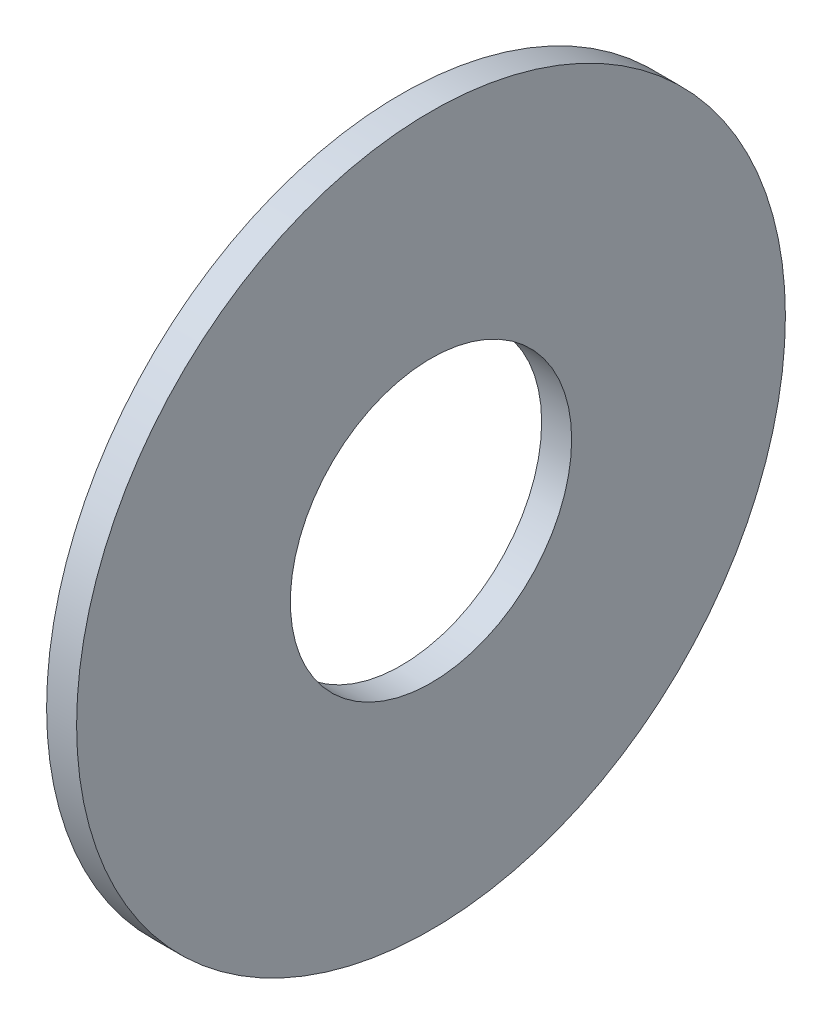
SolidWorks part; units mm, degrees
material "Delrin 2700 NC010, Low Viscosity Acetal Copolymer (SS)"
ref_plane "Front Plane" through (0, 0, 0) normal (0, 0, 1) x (1, 0, 0)
ref_plane "Top Plane" through (0, 0, 0) normal (0, 1, 0) x (1, 0, 0)
ref_plane "Right Plane" through (0, 0, 0) normal (1, 0, 0) x (0, 0, -1)
sketch "Sketch1" plane through (0, 0, 0) normal (1, 0, 0) x (0, 0, -1)
  circle A0 centre (0, 0) radius 2.3813
  circle A1 centre (0, 0) radius 6
  dimension "D1" = 4.7625
  dimension "D2" = 12
extrude "Boss-Extrude1" add sketch "Sketch1" along normal blind 0.508
